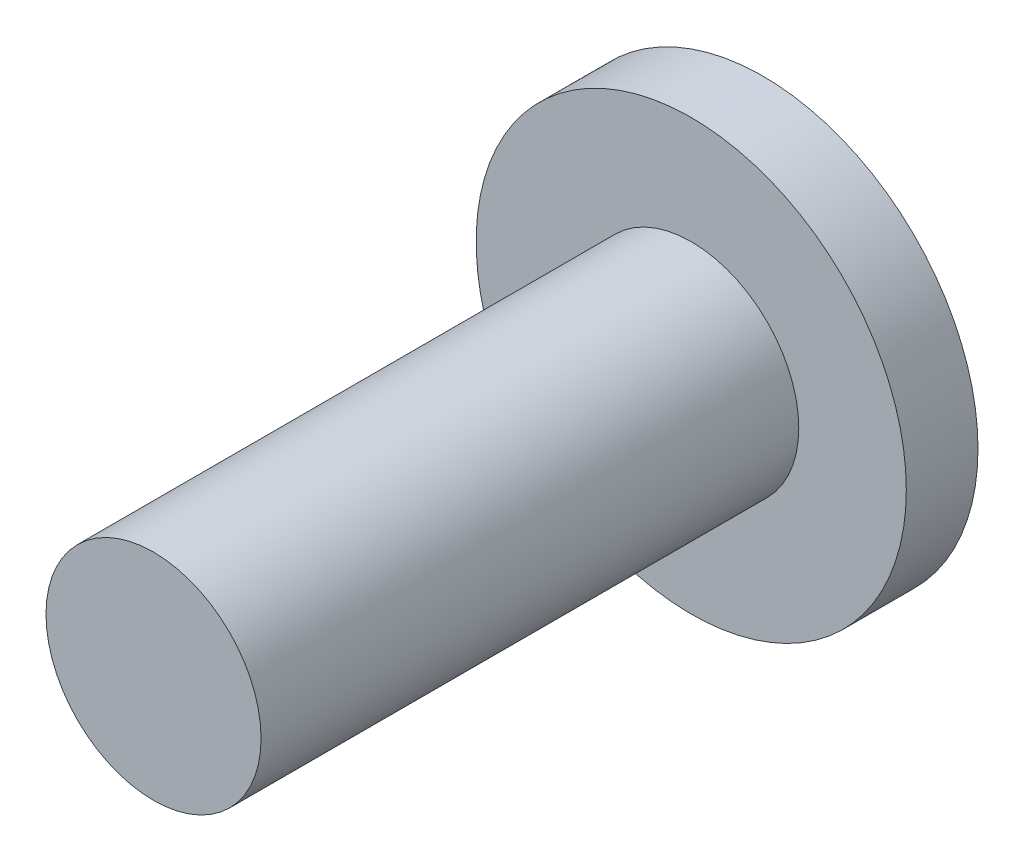
SolidWorks part; units mm, degrees
ref_plane "Front Plane" through (0, 0, 0) normal (0, 0, 1) x (1, 0, 0)
ref_plane "Top Plane" through (0, 0, 0) normal (0, 1, 0) x (1, 0, 0)
ref_plane "Right Plane" through (0, 0, 0) normal (1, 0, 0) x (0, 0, -1)
sketch "Sketch1" plane through (0, 0, 0) normal (0, 0, 1) x (1, 0, 0)
  circle A0 centre (0, 0) radius 6
extrude "Boss-Extrude1" add sketch "Sketch1" along normal blind 2
sketch "Sketch2" plane through (0, 0, 2) normal (0, 0, 1) x (1, 0, 0)
  circle A0 centre (0, 0) radius 3
extrude "Boss-Extrude2" add sketch "Sketch2" along normal blind 15
